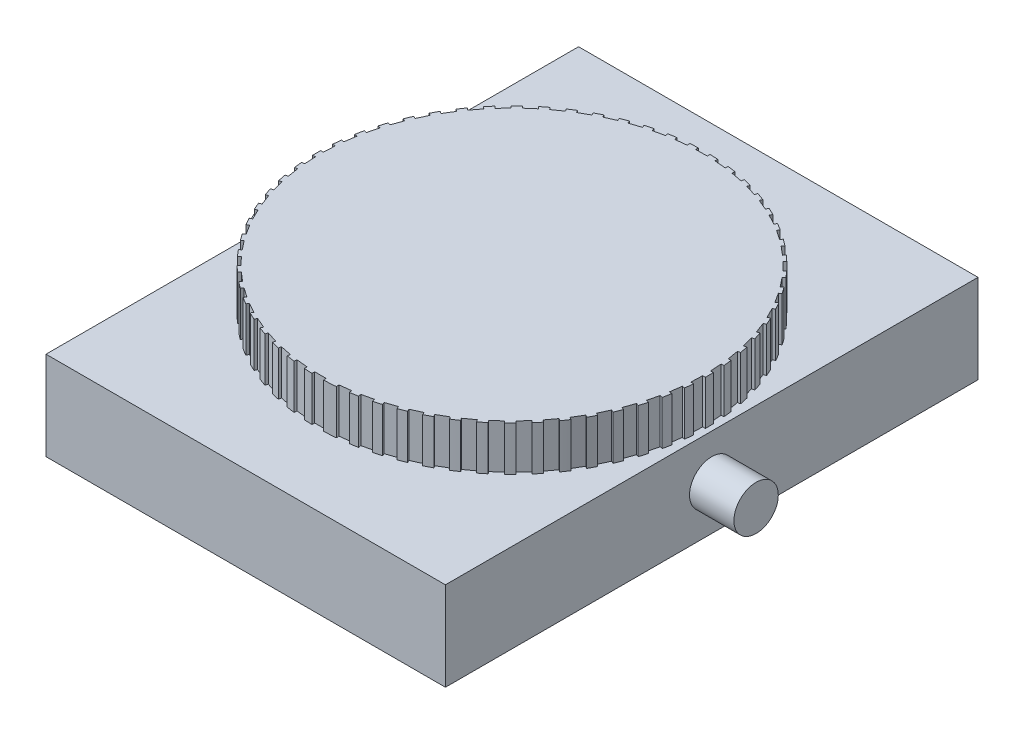
SolidWorks part; units mm, degrees
ref_plane "Front Plane" through (0, 0, 0) normal (0, 0, 1) x (1, 0, 0)
ref_plane "Top Plane" through (0, 0, 0) normal (0, 1, 0) x (1, 0, 0)
ref_plane "Right Plane" through (0, 0, 0) normal (1, 0, 0) x (0, 0, -1)
sketch "Sketch1" plane through (0, 0, 0) normal (0, 1, 0) x (1, 0, 0)
  line L1 (-57.15, -76.2) -> (57.15, -76.2)
  line L2 (-57.15, -76.2) -> (-57.15, 76.2)
  line L3 (-57.15, 76.2) -> (57.15, 76.2)
  line L4 (57.15, -76.2) -> (57.15, 76.2)
  line L5 (-57.15, -76.2) -> (57.15, 76.2) construction
  line L6 (-57.15, 76.2) -> (57.15, -76.2) construction
  point P0 (0, 0)
  dimension "D1" = 114.3
  dimension "D2" = 152.4
extrude "Boss-Extrude1" add sketch "Sketch1" along normal blind 25.4
sketch "Sketch2" plane through (0, 25.4, 0) normal (0, 1, 0) x (1, 0, 0)
  circle A0 centre (0, 0) radius 55.6109
extrude "Boss-Extrude2" add sketch "Sketch2" along normal blind 12.7 separate body
sketch "Sketch3" plane through (0, 25.4, 0) normal (0, 1, 0) x (1, 0, 0)
  line L1 (-1.6391, -54.8086) -> (1.6391, -54.8086)
  line L2 (-1.6391, -54.8086) -> (-1.6391, -61.6043)
  line L3 (-1.6391, -61.6043) -> (1.6391, -61.6043)
  line L4 (1.6391, -54.8086) -> (1.6391, -61.6043)
  line L5 (-1.6391, -54.8086) -> (1.6391, -61.6043) construction
  line L6 (-1.6391, -61.6043) -> (1.6391, -54.8086) construction
  point P0 (0, -58.2065)
extrude "Cut-Extrude1" cut sketch "Sketch3" along normal through all
pattern_circular "CirPattern1" count 62 over 353 about axis through (0, 0, 0) along (0, 1, 0) of "Cut-Extrude1"
sketch "Sketch4" plane through (57.15, 0, 0) normal (1, 0, 0) x (0, 0, -1)
  line L0 (-76.2, 25.4) -> (76.2, 25.4) construction
  line L1 (0, 25.4) -> (0, 0) construction
  line L2 (-76.2, 0) -> (76.2, 0) construction
  circle A0 centre (0, 12.7) radius 6.35
extrude "Boss-Extrude3" add sketch "Sketch4" along normal blind 12.7
mirror "Mirror1" about plane through (0, 0, 0) normal (1, 0, 0) of "Boss-Extrude3"
sketch "Sketch5" plane through (0, 38.1, 0) normal (0, 1, 0) x (1, 0, 0)
  circle A0 centre (0, 0) radius 28.9469 construction
